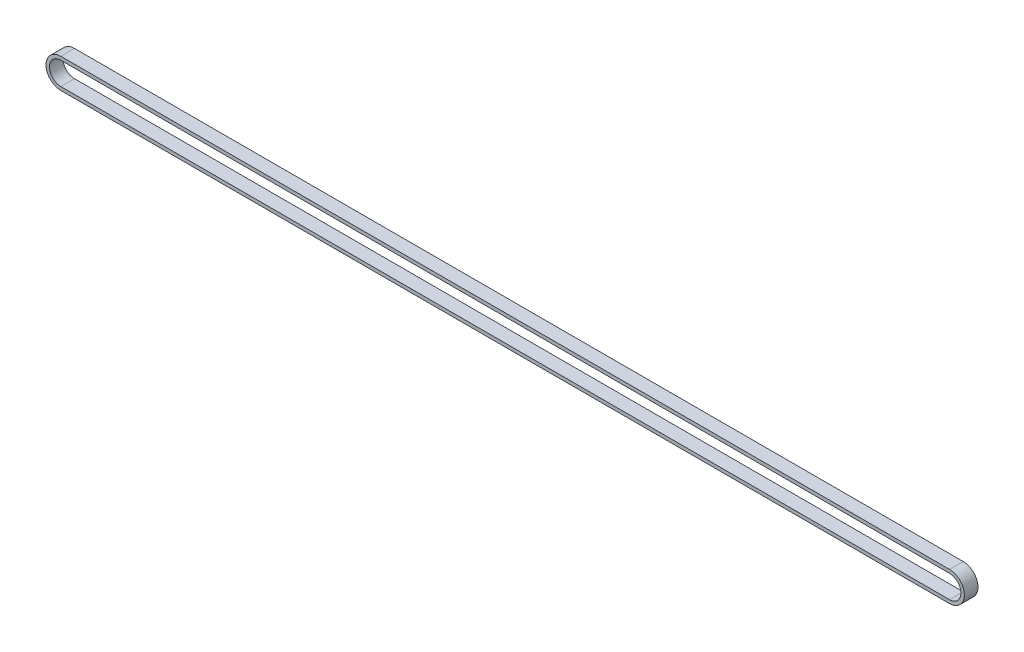
SolidWorks part; units mm, degrees
material "BUTYL"
ref_plane "前视基准面" through (0, 0, 0) normal (0, 0, 1) x (1, 0, 0)
ref_plane "上视基准面" through (0, 0, 0) normal (0, 1, 0) x (1, 0, 0)
ref_plane "右视基准面" through (0, 0, 0) normal (1, 0, 0) x (0, 0, -1)
sketch "草图1" plane through (0, 0, 0) normal (0, 0, 1) x (1, 0, 0)
  line L0 (0, 0) -> (390, 0) construction
  line L1 (0, 5) -> (390, 5)
  line L2 (0, -5) -> (390, -5)
  line L3 (0, 6.5) -> (390, 6.5)
  line L4 (0, -6.5) -> (390, -6.5)
  line L5 (0, -1.5) -> (390, -1.5) construction
  line L6 (0, -1.5) -> (390, -1.5) construction
  arc A0 (0, 5) -> (0, -5) centre (0, 0) ccw
  arc A1 (390, -5) -> (390, 5) centre (390, 0) ccw
  arc A2 (390, -6.5) -> (390, 6.5) centre (390, 0) ccw
  arc A3 (0, 6.5) -> (0, -6.5) centre (0, 0) ccw
  dimension "D1" = 10
  dimension "D2" = 10
  dimension "D3" = 390
  dimension "D4" = 1.5
  dimension "D5" = 1.5
extrude "凸台-拉伸1" add sketch "草图1" along normal blind 6
